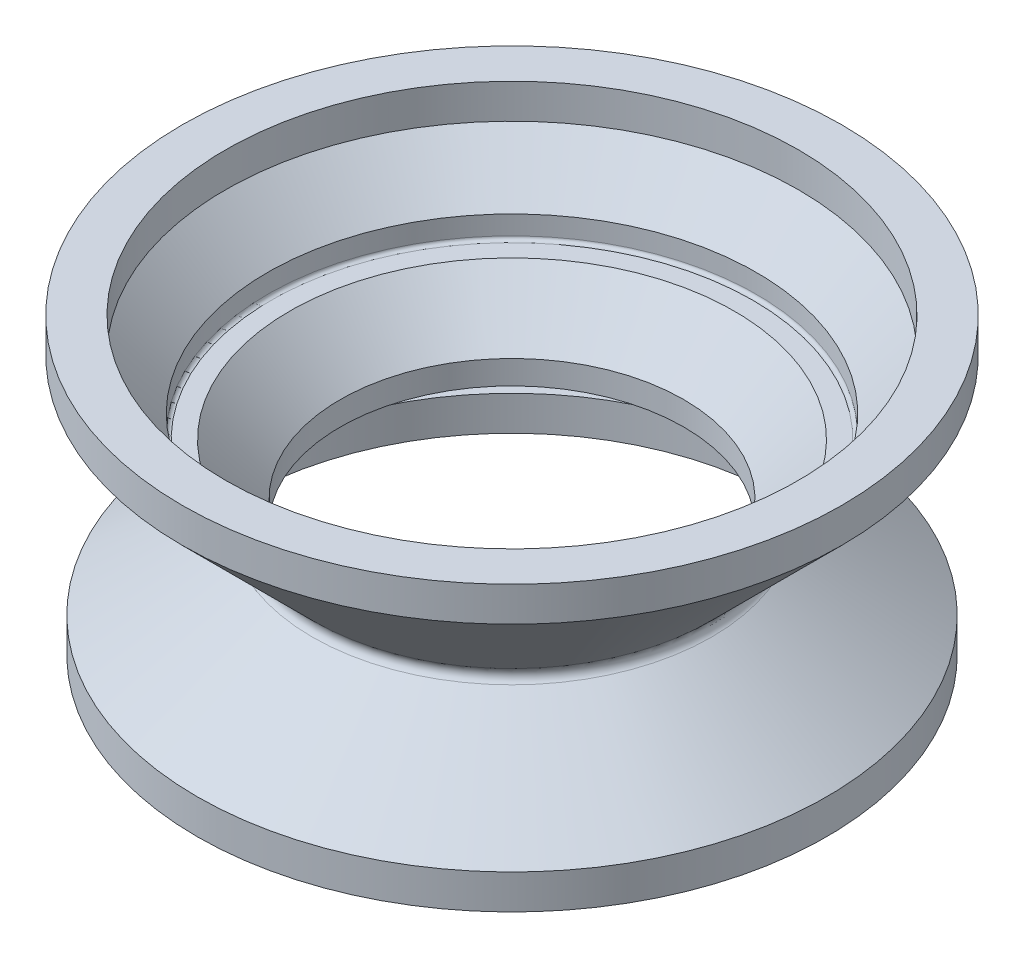
SolidWorks part; units mm, degrees
ref_plane "Front Plane" through (0, 0, 0) normal (0, 0, 1) x (1, 0, 0)
ref_plane "Top Plane" through (0, 0, 0) normal (0, 1, 0) x (1, 0, 0)
ref_plane "Right Plane" through (0, 0, 0) normal (1, 0, 0) x (0, 0, -1)
sketch "Sketch1" plane through (0, 0, 0) normal (0, 0, 1) x (1, 0, 0)
  line L0 (0, 30.1831) -> (0, -35.9724) construction
  line L1 (0, -55) -> (0, 55) construction
  line L2 (-41.2415, 0) -> (38.071, 0) construction
  line L3 (55, 0) -> (-55, 0) construction
  line L4 (-17, 8) -> (-14.1202, 5.0747)
  line L5 (-9.9242, -0.5602) -> (-12.9242, -2.6608)
  line L6 (-16.265, -5) -> (-18.1827, -5)
  line L7 (-18.1827, -5) -> (-11.042, 0)
  line L8 (-11.042, 0) -> (-19.042, 8)
  line L9 (-19.042, 8) -> (-17, 8)
  line L10 (-8.3242, 0) -> (-9.9242, 0) construction
  line L11 (-9.9242, -0.5602) -> (-9.9242, 0.8126)
  line L12 (-9.9242, 0) -> (-12.9242, 0) construction
  line L13 (-9.9242, 0.8126) -> (-9.1242, 0) construction
  line L14 (-9.1242, 0) -> (-9.9242, -0.5602) construction
  line L15 (-12.8437, 3.7781) -> (-11.8672, 3.7781) construction
  line L16 (-12.8437, 3.7781) -> (-14.1202, 3.7781)
  line L17 (-14.1202, 3.7781) -> (-14.8202, 3.7781) construction
  line L18 (-14.1202, 3.7781) -> (-14.1202, 5.0747)
  line L19 (-12.8437, 3.7781) -> (-9.9242, 0.8126)
  line L20 (-14.1202, 5.0747) -> (-12.8437, 3.7781) construction
  line L21 (-12.9242, -2.6608) -> (-13.9453, -2.6608)
  line L22 (-13.9453, -2.6608) -> (-13.9453, -3.3758)
  line L23 (-13.9453, -2.6608) -> (-14.5453, -2.6608) construction
  line L24 (-13.9453, -3.3758) -> (-16.265, -5)
  line L25 (-12.9242, -2.6608) -> (-13.9453, -3.3758) construction
  point P11 (-9.1242, 0)
  dimension "D1" = 17
  dimension "D2" = 45
  dimension "D3" = 35
  dimension "D4" = 8
  dimension "D5" = 5
  dimension "D6" = 1.1
  dimension "D7" = 0.7
  dimension "D8" = 1.6
  dimension "D9" = 3
  dimension "D10" = 0.6
revolve "Revolve1" add sketch "Sketch1" angle 360 about L0
fillet "Fillet3" radius 0.2 1 edges at (0, 3.7781, 14.1202)
fillet "Fillet5" radius 0.1 1 edges at (0, -2.6608, 13.9453)
sketch "Sketch2" plane through (0, 8, 0) normal (0, 1, 0) x (1, 0, 0)
  circle A0 centre (0, 0) radius 19.042 construction
  circle A1 centre (0, 0) radius 19.042
  circle A2 centre (0, 0) radius 16.542
  dimension "D1" = 2.5
extrude "Boss-Extrude1" add sketch "Sketch2" along normal blind 2
sketch "Sketch3" plane through (0, -5, 0) normal (0, -1, 0) x (1, 0, 0)
  circle A0 centre (0, 0) radius 18.1827 construction
  circle A1 centre (0, 0) radius 18.1827
  circle A2 centre (0, 0) radius 15.6827
  dimension "D1" = 2.5
extrude "Boss-Extrude2" add sketch "Sketch3" along normal blind 2
fillet "middle_filllet" radius 0.5 1 edges at (0, 0, 11.042)
